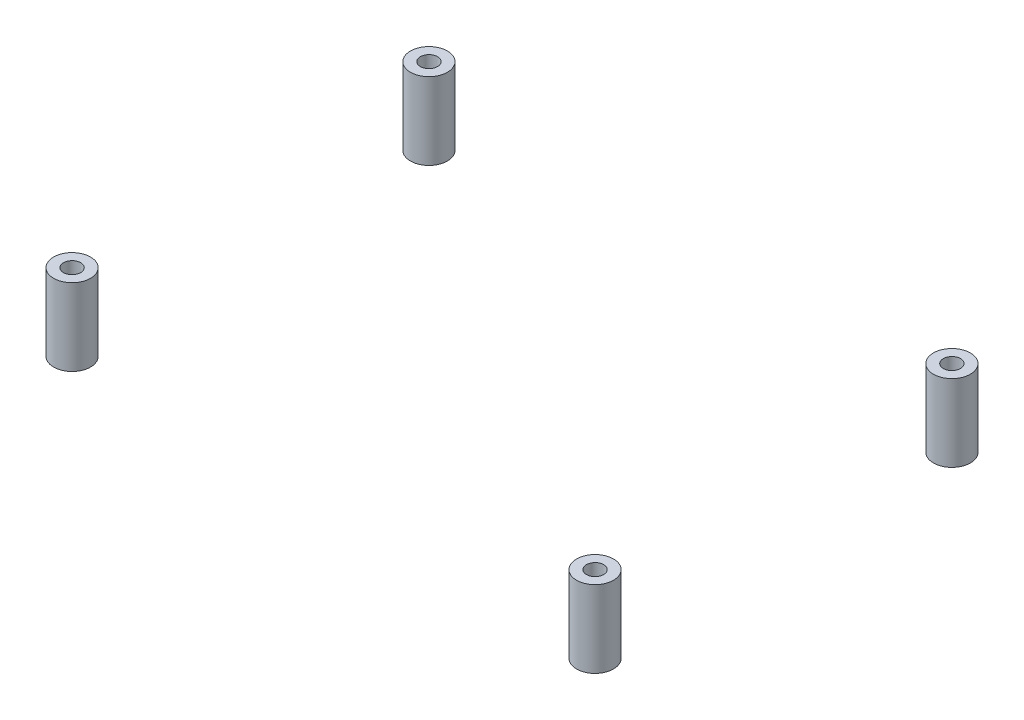
SolidWorks part; units mm, degrees
ref_plane "Front Plane" through (0, 0, 0) normal (0, 0, 1) x (1, 0, 0)
ref_plane "Top Plane" through (0, 0, 0) normal (0, 1, 0) x (1, 0, 0)
ref_plane "Right Plane" through (0, 0, 0) normal (1, 0, 0) x (0, 0, -1)
sketch "Sketch1" plane through (0, 0, 0) normal (0, 1, 0) x (1, 0, 0)
  line L0 (22.2928, 22.4156) -> (22.2928, -35.5844) construction
  line L1 (-20.2072, 22.4156) -> (64.7928, 22.4156)
  line L2 (-20.2072, 22.4156) -> (-20.2072, -35.5844)
  line L3 (-20.2072, -35.5844) -> (64.7928, -35.5844)
  line L4 (64.7928, 22.4156) -> (64.7928, -35.5844)
  line L5 (-20.2072, -6.5844) -> (64.7928, -6.5844) construction
  line L6 (-30.2072, 25.4156) -> (89.7928, 25.4156) construction
  line L7 (94.7928, 25.4156) -> (94.7928, -56.5844) construction
  circle A0 centre (-20.2072, 22.4156) radius 3
  circle A1 centre (64.7928, 22.4156) radius 3
  circle A2 centre (64.7928, -35.5844) radius 3
  circle A3 centre (-20.2072, -35.5844) radius 3
  point P16 (94.7928, -15.5844)
  dimension "D3" = 6
  dimension "D1" = 58
  dimension "D2" = 85
  dimension "D4" = 3
  dimension "D5" = 30
extrude "Boss-Extrude1" add sketch "Sketch1" along normal blind 12.5 contours A3 L2 L3 | A3 L3 L2 | L1 A0 L2 | L2 A0 L1 | L3 A2 L4 | L4 A2 L3 | A1 L1 L4 | A1 L4 L1
sketch "Sketch2" plane through (0, 12.5, 0) normal (0, 1, 0) x (1, 0, 0)
  circle A0 centre (-20.2072, 22.4156) radius 1.4
  circle A1 centre (-20.2072, -35.5844) radius 1.4
  circle A2 centre (64.7928, -35.5844) radius 1.4
  circle A3 centre (64.7928, 22.4156) radius 1.4
  dimension "D1" = 2.8
extrude "Cut-Extrude1" cut sketch "Sketch2" against normal blind 10
